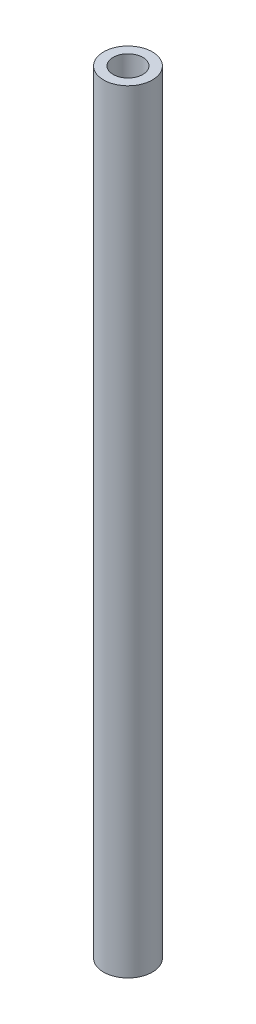
SolidWorks part; units mm, degrees
ref_plane "Front Plane" through (0, 0, 0) normal (0, 0, 1) x (1, 0, 0)
ref_plane "Top Plane" through (0, 0, 0) normal (0, 1, 0) x (1, 0, 0)
ref_plane "Right Plane" through (0, 0, 0) normal (1, 0, 0) x (0, 0, -1)
sketch "Sketch1" plane through (0, 0, 0) normal (0, 1, 0) x (1, 0, 0)
  circle A6 centre (0, 0) radius 0.082
  circle A7 centre (0, 0) radius 0.05
  dimension "D1" = 0.164
  dimension "D2" = 0.1
extrude "Boss-Extrude1" add sketch "Sketch1" along normal blind 2.6
